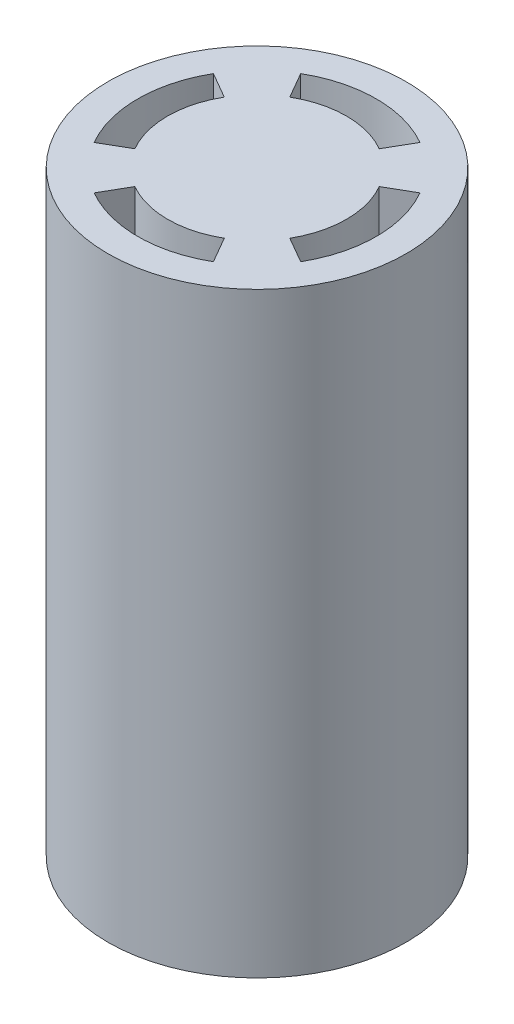
SolidWorks part; units mm, degrees
ref_plane "Front Plane" through (0, 0, 0) normal (0, 0, 1) x (1, 0, 0)
ref_plane "Top Plane" through (0, 0, 0) normal (0, 1, 0) x (1, 0, 0)
ref_plane "Right Plane" through (0, 0, 0) normal (1, 0, 0) x (0, 0, -1)
sketch "Sketch1" plane through (0, 0, 0) normal (0, 1, 0) x (1, 0, 0)
  line L0 (0, 0) -> (0, 5) construction
  line L1 (0, 0) -> (2.5, 4.3301) construction
  line L2 (0, 0) -> (-2.5, 4.3301) construction
  line L3 (-2, 3.4641) -> (-1.5, 2.5981)
  line L4 (1.5, 2.5981) -> (2, 3.4641)
  line L5 (2.5981, -1.5) -> (3.4641, -2)
  line L6 (3.4641, 2) -> (2.5981, 1.5)
  line L7 (-1.5, -2.5981) -> (-2, -3.4641)
  line L8 (2, -3.4641) -> (1.5, -2.5981)
  line L9 (-2.5981, 1.5) -> (-3.4641, 2)
  line L10 (-3.4641, -2) -> (-2.5981, -1.5)
  circle A0 centre (0, 0) radius 5
  arc A1 (-1.5, 2.5981) -> (1.5, 2.5981) centre (0, 0) cw
  arc A2 (-2, 3.4641) -> (2, 3.4641) centre (0, 0) cw
  arc A3 (3.4641, 2) -> (3.4641, -2) centre (0, 0) cw
  arc A4 (2.5981, 1.5) -> (2.5981, -1.5) centre (0, 0) cw
  arc A5 (2, -3.4641) -> (-2, -3.4641) centre (0, 0) cw
  arc A6 (1.5, -2.5981) -> (-1.5, -2.5981) centre (0, 0) cw
  arc A7 (-3.4641, -2) -> (-3.4641, 2) centre (0, 0) cw
  arc A8 (-2.5981, -1.5) -> (-2.5981, 1.5) centre (0, 0) cw
  point P20 (0, 0)
  dimension "D1" = 10
  dimension "D3" = 3
  dimension "D4" = 4
  dimension "D2" = 30
  dimension "D5" = 4
extrude "Boss-Extrude1" add sketch "Sketch1" along normal blind 20
sketch "Sketch2" plane through (0, 0, 0) normal (0, -1, 0) x (1, 0, 0)
  circle A0 centre (0, 0) radius 0.75
  dimension "D1" = 1.5
extrude "Cut-Extrude1" cut sketch "Sketch2" against normal offset from surface (15 mm away) 5 up to face at (0, 20, 5)
